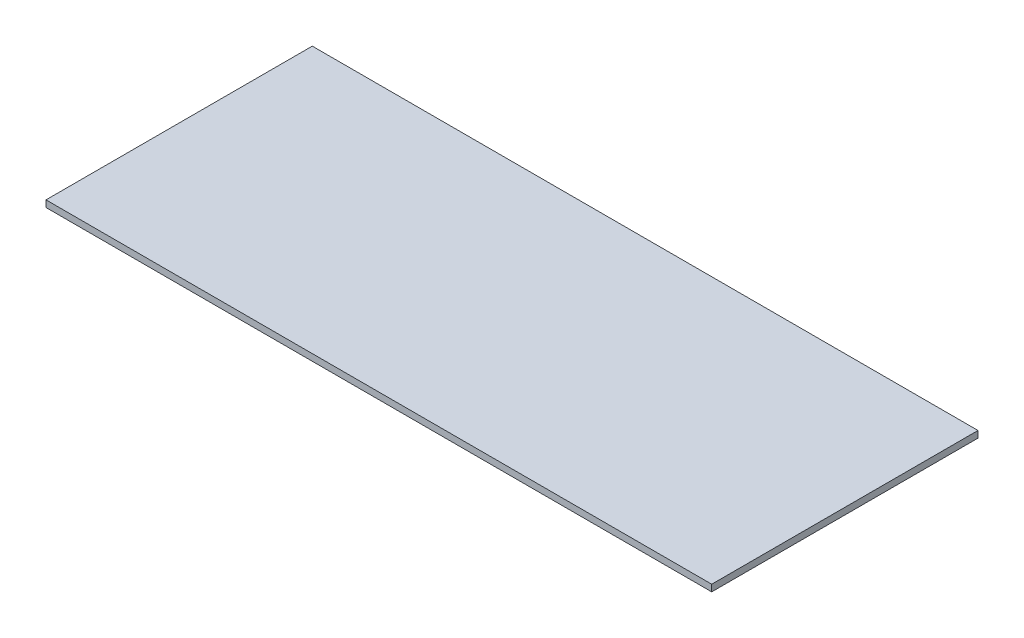
SolidWorks part; units mm, degrees
ref_plane "Front Plane" through (0, 0, 0) normal (0, 0, 1) x (1, 0, 0)
ref_plane "Top Plane" through (0, 0, 0) normal (0, 1, 0) x (1, 0, 0)
ref_plane "Right Plane" through (0, 0, 0) normal (1, 0, 0) x (0, 0, -1)
sketch "Sketch1" plane through (0, 0, 0) normal (0, 1, 0) x (1, 0, 0)
  line L1 (-250, -100) -> (250, -100)
  line L2 (-250, -100) -> (-250, 100)
  line L3 (-250, 100) -> (250, 100)
  line L4 (250, -100) -> (250, 100)
  line L5 (-250, -100) -> (250, 100) construction
  line L6 (-250, 100) -> (250, -100) construction
  point P0 (0, 0)
  dimension "D1" = 200
  dimension "D2" = 500
extrude "Boss-Extrude1" add sketch "Sketch1" along normal blind 5
